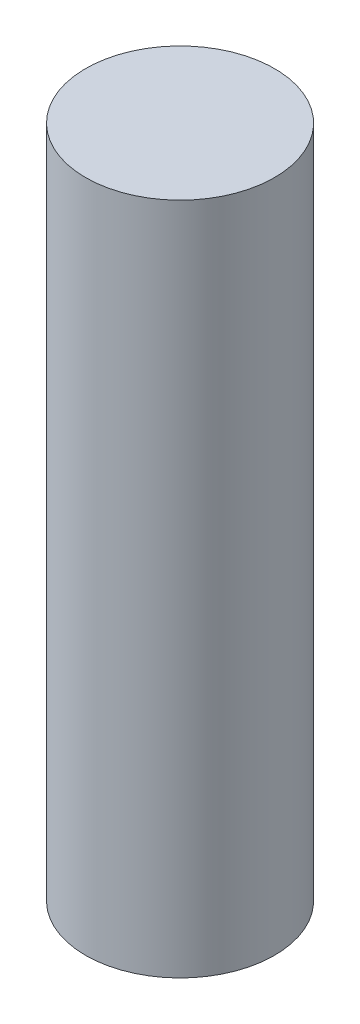
SolidWorks part; units mm, degrees
ref_plane "Plan de face" through (0, 0, 0) normal (0, 0, 1) x (1, 0, 0)
ref_plane "Plan de dessus" through (0, 0, 0) normal (0, 1, 0) x (1, 0, 0)
ref_plane "Plan de droite" through (0, 0, 0) normal (1, 0, 0) x (0, 0, -1)
sketch "Esquisse1" plane through (0, 0, 0) normal (0, 1, 0) x (1, 0, 0)
  circle A0 centre (0, 0) radius 9.15
  dimension "D1" = 18.3
extrude "Boss.-Extru.1" add sketch "Esquisse1" along normal blind 65.25
